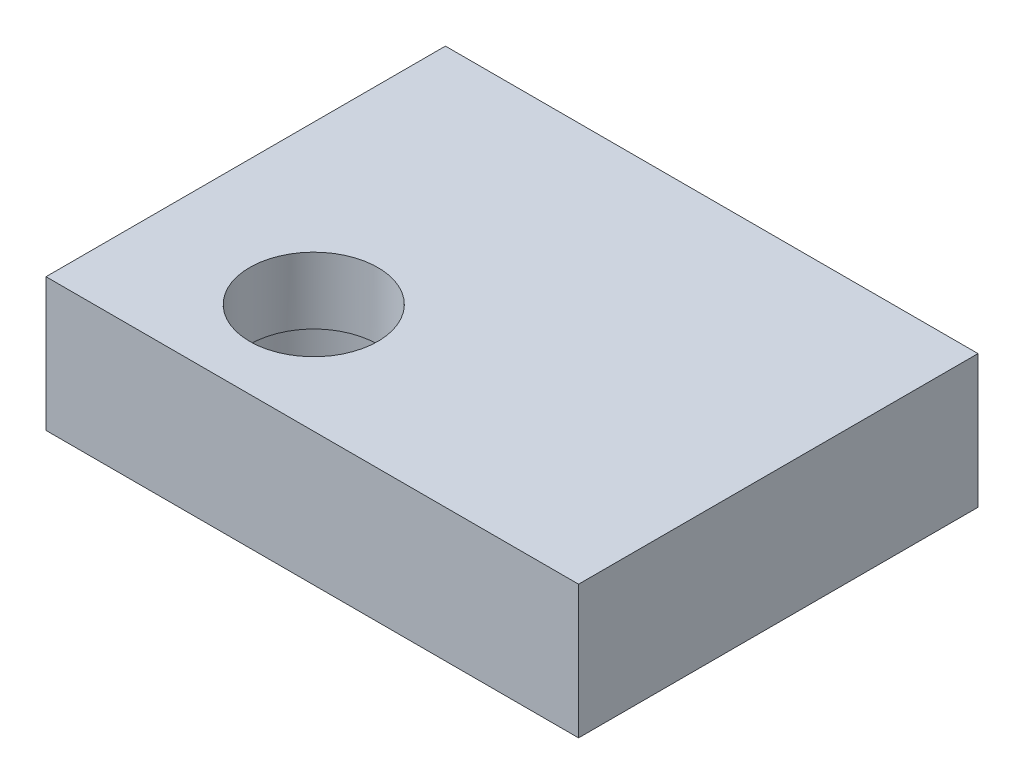
SolidWorks part; units mm, degrees
ref_plane "Front Plane" through (0, 0, 0) normal (0, 0, 1) x (1, 0, 0)
ref_plane "Top Plane" through (0, 0, 0) normal (0, 1, 0) x (1, 0, 0)
ref_plane "Right Plane" through (0, 0, 0) normal (1, 0, 0) x (0, 0, -1)
sketch "Sketch1" plane through (0, 0, 0) normal (0, 1, 0) x (1, 0, 0)
  line L1 (-20, -15) -> (20, -15)
  line L2 (-20, -15) -> (-20, 15)
  line L3 (-20, 15) -> (20, 15)
  line L4 (20, -15) -> (20, 15)
  line L5 (-20, -15) -> (20, 15) construction
  line L6 (-20, 15) -> (20, -15) construction
  point P0 (0, 0)
  dimension "D1" = 40
  dimension "D2" = 30
extrude "Boss-Extrude1" add sketch "Sketch1" along normal blind 10
sketch "Sketch2" plane through (0, 0, 0) normal (0, -1, 0) x (-1, 0, 0)
  line L0 (20, 15) -> (-20, -15) construction
  line L1 (20, -15) -> (-20, 15) construction
  line L2 (20, -15) -> (-20, -15) construction
  line L3 (20, 0) -> (-20, 0) construction
  line L4 (20, 15) -> (20, -15) construction
  line L5 (-20, -15) -> (-20, 15) construction
  line L6 (0, -15) -> (0, 15) construction
  line L7 (-20, 15) -> (20, 15) construction
  circle A0 centre (-13.3333, -10) radius 2
  circle A1 centre (-13.3333, 10) radius 2
  circle A2 centre (13.3333, 10) radius 2
  circle A3 centre (8.14, -6.75) radius 6.3
  dimension "D1" = 4
  dimension "D5" = 12.6
  dimension "D2" = 5
  dimension "D3" = 11.86
  dimension "D4" = 8.25
extrude "Cut-Extrude1" cut sketch "Sketch2" against normal blind 5
sketch "Sketch3" plane through (0, 10, 0) normal (0, 1, 0) x (1, 0, 0)
  line L6 (-20, 15) -> (-20, -15) construction
  line L10 (-20, -15) -> (20, -15) construction
  circle A0 centre (-8.14, -6.75) radius 4.8125
  dimension "D1" = 9.625
  dimension "D2" = 11.86
  dimension "D3" = 8.25
extrude "Cut-Extrude2" cut sketch "Sketch3" against normal up to surface (10 mm away) up to face at (-8.14, 0, 0.45)
